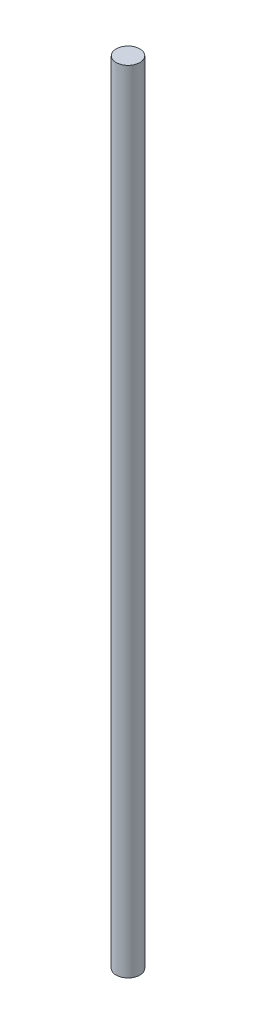
SolidWorks part; units mm, degrees
ref_plane "前视基准面" through (0, 0, 0) normal (0, 0, 1) x (1, 0, 0)
ref_plane "上视基准面" through (0, 0, 0) normal (0, 1, 0) x (1, 0, 0)
ref_plane "右视基准面" through (0, 0, 0) normal (1, 0, 0) x (0, 0, -1)
sketch "草图1" plane through (0, 0, 0) normal (0, 1, 0) x (1, 0, 0)
  circle A0 centre (0, 0) radius 1.5
  dimension "D1" = 3
extrude "凸台-拉伸1" add sketch "草图1" along normal blind 100
